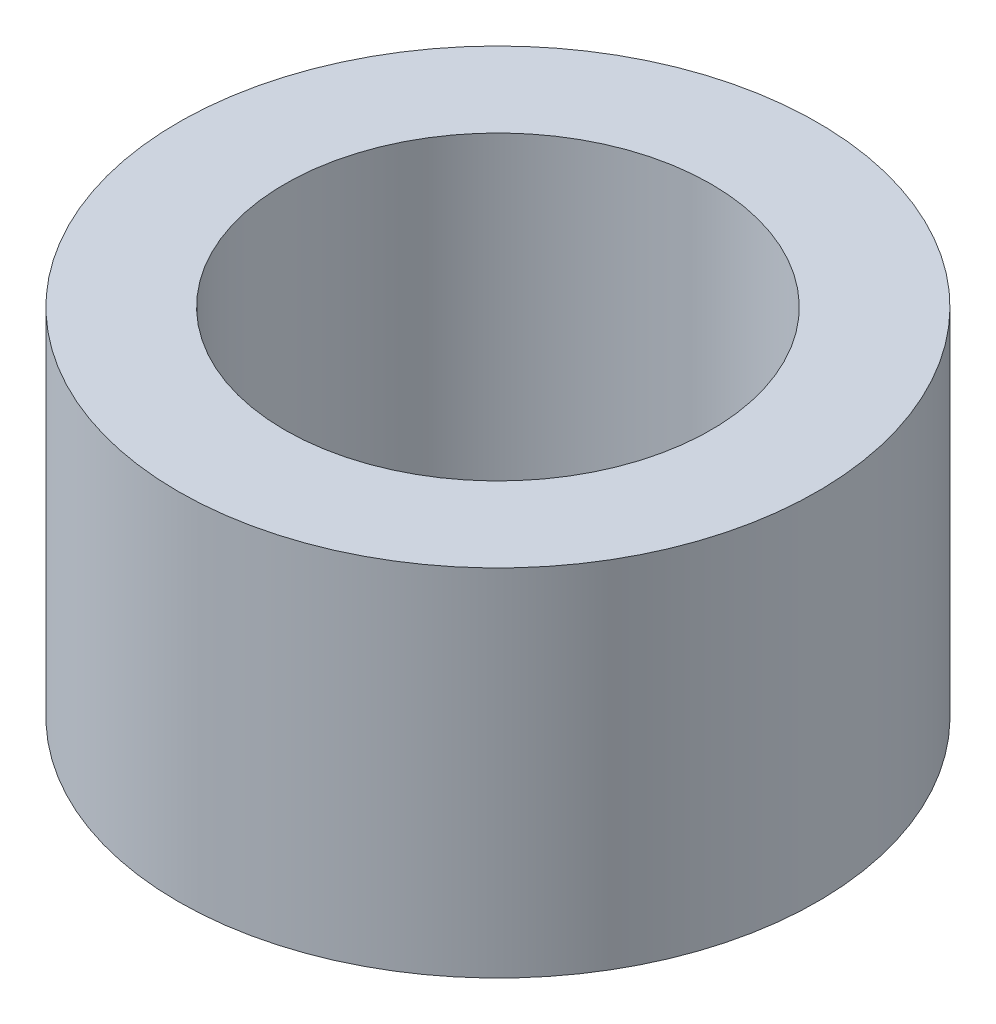
SolidWorks part; units mm, degrees
ref_plane "Front" through (0, 0, 0) normal (0, 0, 1) x (1, 0, 0)
ref_plane "Top" through (0, 0, 0) normal (0, 1, 0) x (1, 0, 0)
ref_plane "Right" through (0, 0, 0) normal (1, 0, 0) x (0, 0, -1)
sketch "Sketch1" plane through (0, 0, 0) normal (0, 1, 0) x (1, 0, 0)
  circle A0 centre (0, 0) radius 9
  circle A1 centre (0, 0) radius 6
  dimension "D1" = 12
  dimension "D2" = 3
extrude "Boss-Extrude1" add sketch "Sketch1" along normal blind 10
